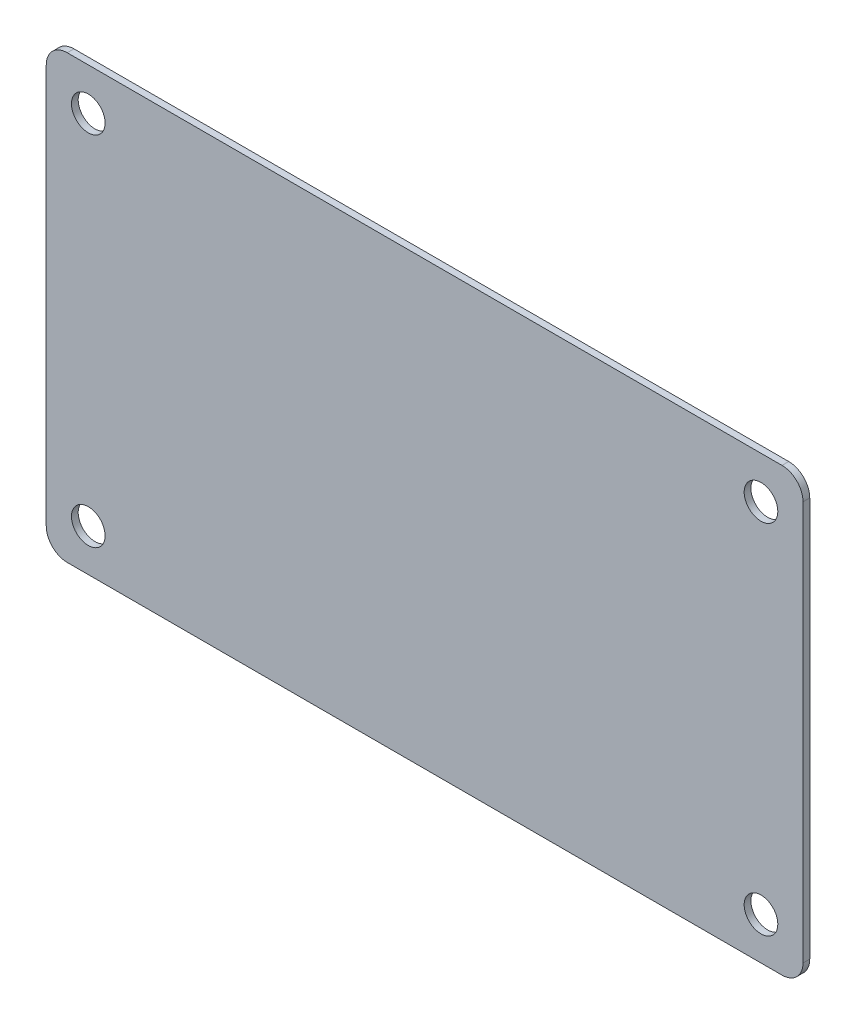
SolidWorks part; units mm, degrees
ref_plane "正面" through (0, 0, 0) normal (0, 0, 1) x (1, 0, 0)
ref_plane "平面" through (0, 0, 0) normal (0, 1, 0) x (1, 0, 0)
ref_plane "右側面" through (0, 0, 0) normal (1, 0, 0) x (0, 0, -1)
sketch "ｽｹｯﾁ1" plane through (0, 0, 0) normal (0, 0, 1) x (1, 0, 0)
  line L1 (5, 0) -> (175, 0)
  line L2 (0, 5) -> (0, 100)
  line L3 (5, 105) -> (175, 105)
  line L4 (180, 5) -> (180, 100)
  arc A0 (0, 100) -> (5, 105) centre (5, 100) cw
  arc A1 (175, 105) -> (180, 100) centre (175, 100) cw
  arc A2 (175, 0) -> (180, 5) centre (175, 5) ccw
  arc A3 (5, 0) -> (0, 5) centre (5, 5) cw
  point P13 (0, 0)
  dimension "D1" = 5
extrude "ﾎﾞｽ - 押し出し1" add sketch "ｽｹｯﾁ1" along normal blind 1.6
sketch "ｽｹｯﾁ2" plane through (0, 0, 0) normal (0, 0, 1) x (1, 0, 0)
  circle A0 centre (10, 10) radius 4
  circle A1 centre (10, 95) radius 4
  circle A2 centre (170, 10) radius 4
  circle A3 centre (170, 95) radius 4
extrude "ｶｯﾄ - 押し出し1" cut sketch "ｽｹｯﾁ2" against normal through all and the other way through all
